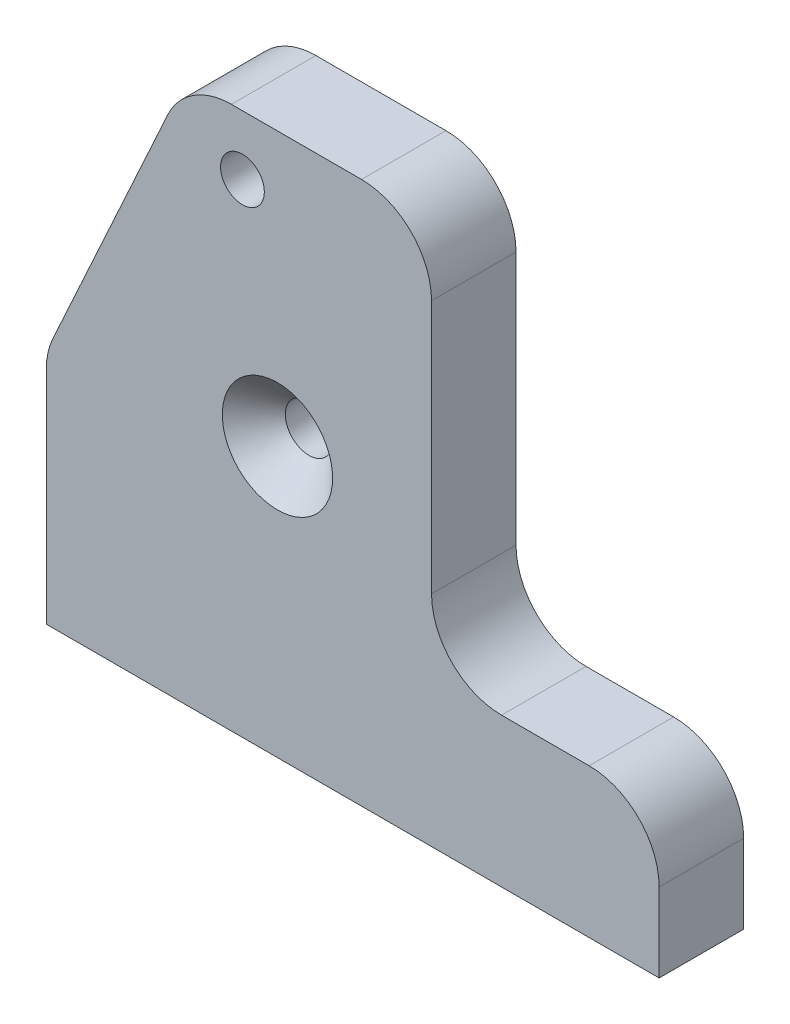
SolidWorks part; units mm, degrees
material "6061 Alloy"
ref_plane "Front" through (0, 0, 0) normal (0, 0, 1) x (1, 0, 0)
ref_plane "Top" through (0, 0, 0) normal (0, 1, 0) x (1, 0, 0)
ref_plane "Right" through (0, 0, 0) normal (1, 0, 0) x (0, 0, -1)
sketch "Sketch1" plane through (0, 0, 0) normal (0, 0, 1) x (1, 0, 0)
  line L0 (0, 0) -> (0, 13.5)
  line L9 (35, 0) -> (0, 0)
  line L15 (8, 31) -> (22, 31)
  line L16 (22, 31) -> (22, 8.5)
  line L17 (22, 8.5) -> (35, 8.5)
  line L18 (35, 8.5) -> (35, 0)
  line L22 (8, 31) -> (0, 13.5)
  dimension "D3" = 13.5
  dimension "D1" = 35
  dimension "D2" = 13
  dimension "D4" = 14
  dimension "D5" = 31
  dimension "D6" = 8.5
extrude "Boss-Extrude1" add sketch "Sketch1" along normal blind 4.826
hole_wizard "M3x0.5 Tapped Hole2" positions "Sketch13" profile "Sketch14" tap size "M3x0.5" standard "ANSI Metric" end condition through all
sketch "Sketch13" plane through (0, 0, 4.826) normal (0, 0, 1) x (1, 0, 0)
  line L2 (35, 0) -> (0, 0) construction
  point P5 (11.2, 27.6)
  dimension "D1" = 27.6
  dimension "D2" = 11.2
sketch "Sketch14" plane through (11.2, 27.6, 4.826) normal (1, 0, 0) x (0, -1, 0)
  line L0 (0, 0) -> (0, 4.826)
  line L1 (0, 4.826) -> (1.25, 4.826)
  line L2 (1.25, 4.826) -> (1.25, 0)
  line L5 (1.25, 0) -> (0, 0)
  line L11 (0, -6.35) -> (0, 107.95) construction
  dimension "Thru Tap Drill Dia." = 2.5
  dimension "Thru Tap Drill Depth" = 4.826
cosmetic thread "Hole Thread1" parameters "D2"=3
sketch "Sketch16" plane through (0, 0, 0) normal (0, -1, 0) x (1, 0, 0)
  line L0 (0, 4.826) -> (0, 0) construction
  line L3 (0, 2.413) -> (42.6944, 2.413) construction
  point P0 (28.73, 2.413)
  point P1 (16.73, 2.413)
  dimension "D1" = 16.73
  dimension "D2" = 12
hole_wizard "M3x0.5 Tapped Hole3" positions "Sketch17" profile "Sketch18" tap size "M3x0.5" standard "ANSI Metric"
sketch "Sketch17" plane through (0, 0, 0) normal (0, -1, 0) x (-1, 0, 0)
  point P0 (-16.73, -2.413)
  point P3 (-28.73, -2.413)
sketch "Sketch18" plane through (16.73, 0, 2.413) normal (1, 0, 0) x (0, 0, -1)
  line L0 (0, 0) -> (0, 5.7511)
  line L1 (0, 5.7511) -> (1.25, 5)
  line L2 (1.25, 5) -> (1.25, 0)
  line L5 (1.25, 0) -> (0, 0)
  line L10 (0, 5.7511) -> (-1.25, 5) construction
  line L11 (0, -6.35) -> (0, 107.95) construction
  dimension "Tap Drill Dia." = 2.5
  dimension "Tap Drill Depth" = 5
  dimension "Drill Angle" = 118
chamfer "Chamfer1" [suppressed] distance 13 distance2 10
fillet "Fillet2" radius 4 5 edges at (35, 8.5, 2.413) (22, 8.5, 2.413) (22, 31, 2.413) (0, 13.5, 2.413) (8, 31, 2.413)
sketch "Sketch19" plane through (0, 0, 4.826) normal (0, 0, 1) x (1, 0, 0)
  line L0 (11.2, 27.6) -> (11.2, 15.4)
  line L1 (11.2, 15.4) -> (13.2, 15.4)
  circle A0 centre (13.2, 15.4) radius 1.25
  dimension "D3" = 2.5
  dimension "D1" = 12.2
  dimension "D2" = 2
extrude "Cut-Extrude1" cut sketch "Sketch19" against normal blind 10
hole_wizard "CSK for M3 Flat Head Machine Screw1" positions "Sketch20" profile "Sketch22" countersink size "M3" standard "ANSI Metric" end condition through all
sketch "Sketch20" plane through (0, 0, 4.826) normal (0, 0, 1) x (1, 0, 0)
  point P0 (13.2, 15.4)
sketch "Sketch22" plane through (13.2, 15.4, 4.826) normal (1, 0, 0) x (0, -1, 0)
  line L0 (0, 0) -> (0, 4.826)
  line L1 (0, 4.826) -> (1.35, 4.826)
  line L2 (1.35, 4.826) -> (1.35, 1.8)
  line L3 (1.35, 1.8) -> (3.15, 0)
  line L5 (3.15, 0) -> (0, 0)
  line L6 (-1.35, 1.8) -> (-3.15, 0) construction
  line L11 (0, -6.35) -> (0, 107.95) construction
  dimension "Thru Hole Dia." = 2.7
  dimension "Thru Hole Depth" = 4.826
  dimension "Near C'Sink Dia." = 6.3
  dimension "Near C'Sink Angle" = 90
